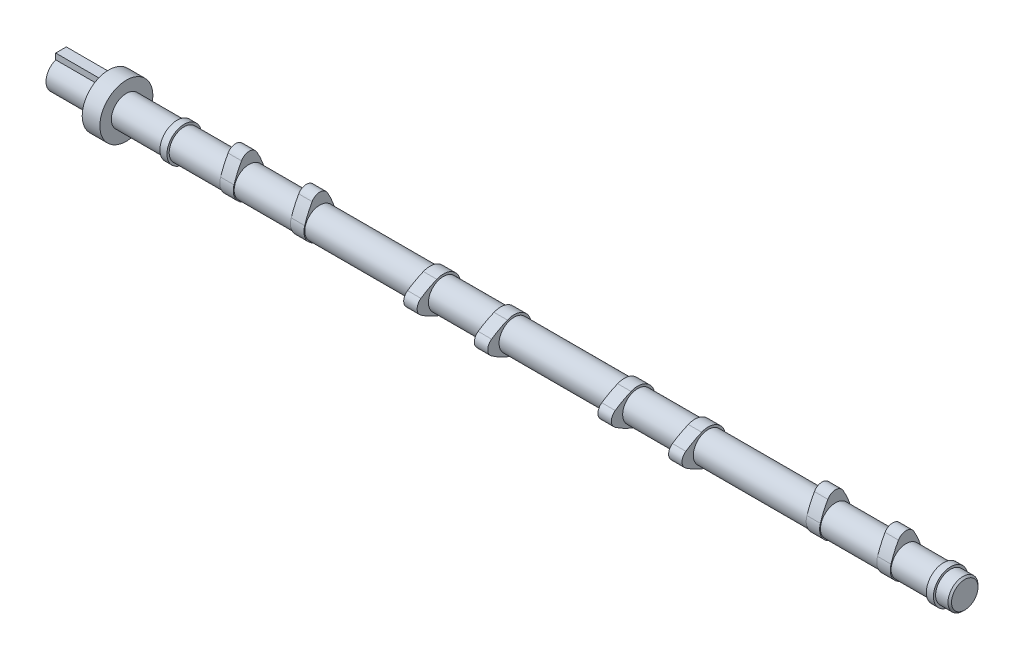
SolidWorks part; units mm, degrees
ref_plane "Alzado" through (0, 0, 0) normal (0, 0, 1) x (1, 0, 0)
ref_plane "Planta" through (0, 0, 0) normal (0, 1, 0) x (1, 0, 0)
ref_plane "Vista lateral" through (0, 0, 0) normal (1, 0, 0) x (0, 0, -1)
sketch "Croquis1" plane through (0, 0, 0) normal (0, 0, 1) x (1, 0, 0)
  line L0 (0, 0) -> (580, 0)
  line L1 (0, 0) -> (0, 8.5)
  line L2 (0, 8.5) -> (580, 8.5) construction
  line L3 (580, 8.5) -> (580, 0)
  line L4 (0, 8.5) -> (580, 8.5)
  dimension "D1" = 580
  dimension "D2" = 17
revolve "Revolución1" add sketch "Croquis1" angle 360 about L2
sketch "Croquis2" plane through (580, 0, 0) normal (1, 0, 0) x (0, 0, -1)
  circle A0 centre (0, 8.5) radius 31.2943
  circle A1 centre (0, 8.5) radius 8.5 construction
sketch "Croquis3" plane through (580, 0, 0) normal (1, 0, 0) x (0, 0, -1)
sketch "Croquis4" plane through (580, 0, 0) normal (1, 0, 0) x (0, 0, -1)
  circle A0 centre (0, 8.5) radius 9.75
  dimension "D1" = 19.5
extrude "Saliente-Extruir1" add sketch "Croquis4" against normal blind 4
pattern_linear "MatrizL1" count 2 spacing 442 along (-1, 0, 0) of "Saliente-Extruir1"
ref_plane "Plano1" through (171, 0, 0) normal (1, 0, 0) x (0, 0, -1)
sketch "Croquis5" plane through (171, 0, 0) normal (1, 0, 0) x (0, 0, -1)
  line L0 (0, 8.5) -> (0, 23.4) construction
  arc A1 (-8.5769, 11.2272) -> (8.5769, 11.2272) centre (0, 8.5) ccw
  arc A2 (4.3414, 20.8804) -> (-4.3414, 20.8804) centre (0, 18.4) ccw
  arc A3 (-4.3414, 20.8804) -> (-8.5769, 11.2272) centre (39.0724, -3.9237) ccw
  arc A4 (4.3414, 20.8804) -> (8.5769, 11.2272) centre (-39.0724, -3.9237) cw
  point P6 (0, 23.4)
  dimension "D1" = 14.9
  dimension "D2" = 10
  dimension "D3" = 18
  dimension "D4" = 100
extrude "Saliente-Extruir3" add sketch "Croquis5" along normal blind 3.8 and the other way blind 3.8
pattern_linear "MatrizL2" count 2 spacing 40 along (1, 0, 0) of "Saliente-Extruir3"
pattern_linear "MatrizL3" count 2 spacing 332 along (1, 0, 0) of "MatrizL2", "Saliente-Extruir3"
ref_plane "Plano2" through (281, 0, 0) normal (1, 0, 0) x (0, 0, -1)
sketch "Croquis6" plane through (281, 0, 0) normal (1, 0, 0) x (0, 0, -1)
  line L0 (0, 23.4) -> (0, 8.5) construction
  line L1 (0, 8.5) -> (-14.9, 8.5) construction
  arc A0 (4.3414, 20.8804) -> (-4.3414, 20.8804) centre (0, 18.4) ccw construction
  arc A1 (-12.7224, 12.6272) -> (-12.7224, 4.3728) centre (-9.9, 8.5) ccw
  circle A2 centre (0, 8.5) radius 8.5 construction
  circle A3 centre (0, 8.5) radius 9.75 construction
  arc A4 (-3.755, -0.4979) -> (-3.755, 17.4979) centre (0, 8.5) ccw
  arc A5 (-12.7224, 4.3728) -> (-3.755, -0.4979) centre (15.5014, 45.6452) ccw
  arc A6 (-3.755, 17.4979) -> (-12.7224, 12.6272) centre (15.5014, -28.6452) ccw
  circle A7 centre (0, 8.5) radius 8.5
  dimension "D1" = 10
  dimension "D2" = 50
  dimension "D3" = 100
extrude "Saliente-Extruir4" add sketch "Croquis6" against normal blind 3.8 and the other way blind 3.8
pattern_linear "MatrizL4" count 2 spacing 40 along (1, 0, 0) of "Saliente-Extruir4"
pattern_linear "MatrizL5" count 2 spacing 110 along (1, 0, 0) of "MatrizL4", "Saliente-Extruir4"
sketch "Croquis7" plane through (580, 0, 0) normal (1, 0, 0) x (0, 0, -1)
  circle A1 centre (0, 8.5) radius 9.75
  circle A2 centre (0, 8.5) radius 9.75
  dimension "D1" = 0
extrude "Cortar-Extruir1" cut sketch "Croquis7" against normal blind 12
sketch "Croquis8" plane through (568, 0, 0) normal (1, 0, 0) x (0, 0, -1)
  circle A0 centre (0, 8.5) radius 9.75
  dimension "D1" = 19.5
extrude "Saliente-Extruir5" add sketch "Croquis8" along normal blind 4
sketch "Croquis9" plane through (572, 0, 0) normal (1, 0, 0) x (0, 0, -1)
  circle A0 centre (0, 8.5) radius 8.5
  dimension "D1" = 17
extrude "Saliente-Extruir6" add sketch "Croquis9" along normal blind 8
chamfer "Chaflán1" distance 1 angle 45 1 edges at (580, 8.5, -8.5)
ref_plane "Plano3" through (100.25, 0, 0) normal (-1, 0, 0) x (0, 0, 1)
sketch "Croquis10" plane through (100.25, 0, 0) normal (-1, 0, 0) x (0, 0, 1)
  circle A0 centre (0, 8.5) radius 15
  dimension "D1" = 30
extrude "Saliente-Extruir7" add sketch "Croquis10" along normal blind 5 and the other way blind 5
sketch "Croquis11" plane through (95.25, 0, 0) normal (-1, 0, 0) x (0, 0, 1)
  line L0 (0, 8.5) -> (0, 16.453) construction
  line L1 (-3, 16.453) -> (3, 16.453)
  line L2 (-3, 16.453) -> (-3, 19.803)
  line L3 (-3, 19.803) -> (3, 19.803)
  line L4 (3, 16.453) -> (3, 19.803)
  line L5 (0, 16.453) -> (0, 19.803) construction
  circle A0 centre (0, 8.5) radius 8.5 construction
  dimension "D1" = 3.35
  dimension "D2" = 6
extrude "Saliente-Extruir8" add sketch "Croquis11" along normal blind 40
ref_plane "Plano4" through (68.25, 0, 0) normal (-1, 0, 0) x (0, 0, 1)
sketch "Croquis12" plane through (0, 0, 0) normal (-1, 0, 0) x (0, 0, 1)
  circle A0 centre (1.3419, 8.1538) radius 47.2471
extrude "Cortar-Extruir2" cut sketch "Croquis12" against normal up to surface (68.25 mm away)
sketch "Croquis13" plane through (68.25, 0, 0) normal (-1, 0, 0) x (0, 0, 1)
  point P0 (0, 8.5)
hole_wizard "Taladro de margen para M71" positions "Croquis3D1" profile "Croquis14" hole size "M7" standard "Ansi Metric"
sketch3d "Croquis3D1"
  point P0 (68.25, 8.5, 0)
sketch "Croquis14" plane through (68.25, 8.5, 0) normal (0, 1, 0) x (0, 0, 1)
  line L0 (0, 0) -> (0, 32.2833)
  line L1 (0, 32.2833) -> (3.8, 30)
  line L2 (3.8, 30) -> (3.8, 0)
  line L5 (3.8, 0) -> (0, 0)
  line L10 (0, 32.2833) -> (-3.8, 30) construction
  line L11 (0, -6.35) -> (0, 107.95) construction
  dimension "Diámetro de taladro" = 7.6
  dimension "Profundidad de taladro" = 30
  dimension "Ángulo de perforador" = 118
